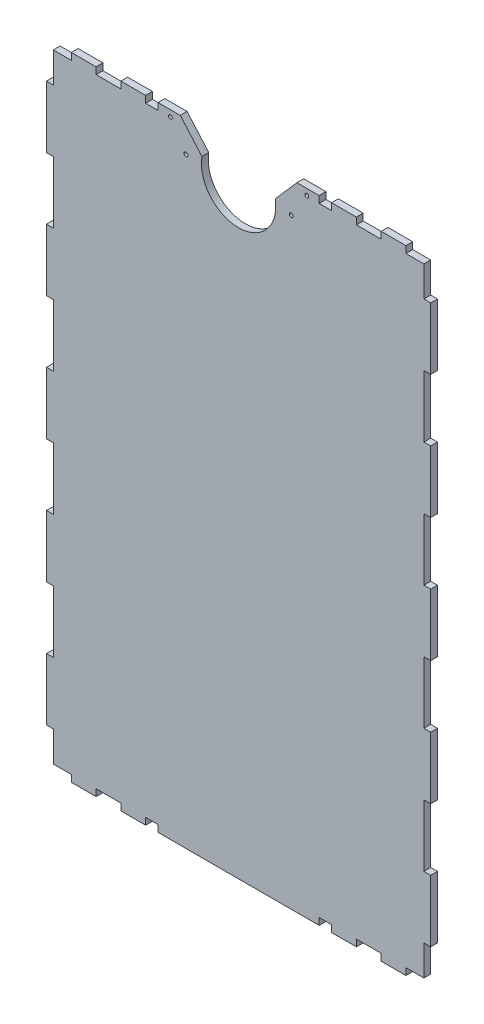
SolidWorks part; units mm, degrees
material "ﾁｰｸ材"
ref_plane "正面" through (0, 0, 0) normal (0, 0, 1) x (1, 0, 0)
ref_plane "平面" through (0, 0, 0) normal (0, 1, 0) x (1, 0, 0)
ref_plane "右側面" through (0, 0, 0) normal (1, 0, 0) x (0, 0, -1)
sketch "ｽｹｯﾁ1" plane through (0, 0, 0) normal (0, 0, 1) x (1, 0, 0)
  line L1 (155, 255) -> (-155, 255)
  line L2 (155, 255) -> (155, -255)
  line L3 (155, -255) -> (-155, -255)
  line L4 (-155, 255) -> (-155, -255)
  line L5 (155, 255) -> (-155, -255) construction
  line L6 (155, -255) -> (-155, 255) construction
  point P0 (0, 0)
  dimension "D1" = 310
  dimension "D2" = 510
extrude "ﾎﾞｽ - 押し出し1" add sketch "ｽｹｯﾁ1" along normal blind 5.5
sketch "ｽｹｯﾁ2" plane through (0, 0, 5.5) normal (0, 0, 1) x (1, 0, 0)
  line L0 (155, -255) -> (155, 255) construction
  line L1 (155, 25) -> (149.5, 25)
  line L2 (155, 25) -> (155, 75)
  line L3 (155, 75) -> (149.5, 75)
  line L4 (149.5, 25) -> (149.5, 75)
  line L9 (155, -75) -> (149.5, -75)
  line L10 (155, -75) -> (155, -25)
  line L11 (155, -25) -> (149.5, -25)
  line L12 (149.5, -75) -> (149.5, -25)
  line L13 (155, 125) -> (149.5, 125)
  line L14 (155, 125) -> (155, 175)
  line L15 (155, 175) -> (149.5, 175)
  line L16 (149.5, 125) -> (149.5, 175)
  line L17 (155, -175) -> (149.5, -175)
  line L18 (155, -175) -> (155, -125)
  line L19 (155, -125) -> (149.5, -125)
  line L20 (149.5, -175) -> (149.5, -125)
  line L21 (155, 225) -> (149.5, 225)
  line L22 (155, 225) -> (155, 275)
  line L23 (155, 275) -> (149.5, 275)
  line L24 (149.5, 225) -> (149.5, 275)
  line L25 (155, -275) -> (149.5, -275)
  line L26 (155, -275) -> (155, -225)
  line L27 (155, -225) -> (149.5, -225)
  line L28 (149.5, -275) -> (149.5, -225)
  line L29 (-149.5, 25) -> (-155, 25)
  line L30 (-149.5, 25) -> (-149.5, 75)
  line L31 (-149.5, 75) -> (-155, 75)
  line L32 (-155, 25) -> (-155, 75)
  line L33 (-149.5, -75) -> (-155, -75)
  line L34 (-149.5, -75) -> (-149.5, -25)
  line L35 (-149.5, -25) -> (-155, -25)
  line L36 (-155, -75) -> (-155, -25)
  line L37 (-149.5, 125) -> (-155, 125)
  line L38 (-149.5, 125) -> (-149.5, 175)
  line L39 (-149.5, 175) -> (-155, 175)
  line L40 (-155, 125) -> (-155, 175)
  line L41 (-149.5, -175) -> (-155, -175)
  line L42 (-149.5, -175) -> (-149.5, -125)
  line L43 (-149.5, -125) -> (-155, -125)
  line L44 (-155, -175) -> (-155, -125)
  line L45 (-149.5, 225) -> (-155, 225)
  line L46 (-149.5, 225) -> (-149.5, 275)
  line L47 (-149.5, 275) -> (-155, 275)
  line L48 (-155, 225) -> (-155, 275)
  line L49 (-149.5, -275) -> (-155, -275)
  line L50 (-149.5, -275) -> (-149.5, -225)
  line L51 (-149.5, -225) -> (-155, -225)
  line L52 (-155, -275) -> (-155, -225)
  line L53 (-155, 255) -> (-155, -255) construction
  point P53 (-152.25, 25)
  dimension "D1" = 5.5
  dimension "D2" = 50
  dimension "D3" = 25
  dimension "D4" = 50
  dimension "D5" = 50
  dimension "D6" = 50
  dimension "D7" = 50
  dimension "D8" = 50
  dimension "D9" = 5.5
  dimension "D10" = 50
  dimension "D11" = 50
  dimension "D12" = 50
  dimension "D13" = 50
  dimension "D14" = 50
  dimension "D15" = 50
  dimension "D16" = 25
extrude "ｶｯﾄ - 押し出し1" cut sketch "ｽｹｯﾁ2" against normal through all
sketch "ｽｹｯﾁ3" plane through (0, 0, 5.5) normal (0, 0, 1) x (1, 0, 0)
  line L0 (47.0333, 255) -> (29.5804, 235)
  line L2 (149.5, 255) -> (-149.5, 255) construction
  line L3 (47.0333, 255) -> (-47.0333, 255)
  line L4 (-47.0333, 255) -> (-29.5804, 235)
  arc A1 (29.5804, 235) -> (-29.5804, 235) centre (0, 230) cw
  dimension "D1" = 30
  dimension "D2" = 25
  dimension "D3" = 19
  dimension "D4" = 19
  dimension "D5" = 5
  dimension "D6" = 5
extrude "ｶｯﾄ - 押し出し2" cut sketch "ｽｹｯﾁ3" against normal through all
sketch "ｽｹｯﾁ5" plane through (0, 0, 5.5) normal (0, 0, 1) x (1, 0, 0)
  circle A0 centre (-42.5, 230) radius 1.6
  circle A1 centre (42.5, 230) radius 1.6
  point P4 (0, 230)
  dimension "D1" = 3.2
  dimension "D2" = 42.5
  dimension "D3" = 42.5
extrude "ｶｯﾄ - 押し出し3" cut sketch "ｽｹｯﾁ5" against normal through all
sketch "ｽｹｯﾁ6" plane through (0, 0, 5.5) normal (0, 0, 1) x (1, 0, 0)
  line L0 (149.5, 255) -> (47.0333, 255) construction
  circle A0 centre (55, 250) radius 1.55
  circle A1 centre (-55, 250) radius 1.55
  dimension "D1" = 3.1
  dimension "D3" = 5
  dimension "D2" = 55
  dimension "D4" = 55
extrude "ｶｯﾄ - 押し出し4" cut sketch "ｽｹｯﾁ6" against normal through all
sketch "ｽｹｯﾁ7" plane through (0, 0, 5.5) normal (0, 0, 1) x (1, 0, 0)
  line L0 (149.5, 255) -> (47.0333, 255) construction
  line L1 (135, 255) -> (155, 255)
  line L2 (135, 255) -> (135, 249.5)
  line L3 (135, 249.5) -> (155, 249.5)
  line L4 (155, 255) -> (155, 249.5)
  line L5 (155, 175) -> (155, 225) construction
  line L6 (95, 255) -> (95, 249.5)
  line L7 (95, 255) -> (115, 255)
  line L8 (115, 255) -> (115, 249.5)
  line L9 (95, 249.5) -> (115, 249.5)
  line L10 (0, 0) -> (0, 80.2112) construction
  line L11 (75, 255) -> (65, 255)
  line L12 (75, 255) -> (75, 249.5)
  line L13 (75, 249.5) -> (65, 249.5)
  line L14 (65, 255) -> (65, 249.5)
  line L15 (0, 0) -> (-49.6238, 0) construction
  line L16 (-75, 249.5) -> (-65, 249.5)
  line L17 (-65, 255) -> (-65, 249.5)
  line L18 (-75, 255) -> (-65, 255)
  line L19 (-75, 255) -> (-75, 249.5)
  line L20 (-95, 255) -> (-115, 255)
  line L21 (-115, 255) -> (-115, 249.5)
  line L22 (-95, 249.5) -> (-115, 249.5)
  line L23 (-95, 255) -> (-95, 249.5)
  line L24 (-135, 249.5) -> (-155, 249.5)
  line L25 (-155, 255) -> (-155, 249.5)
  line L26 (-135, 255) -> (-155, 255)
  line L27 (-135, 255) -> (-135, 249.5)
  line L28 (-135, -255) -> (-135, -249.5)
  line L29 (-135, -255) -> (-155, -255)
  line L30 (-155, -255) -> (-155, -249.5)
  line L31 (-135, -249.5) -> (-155, -249.5)
  line L32 (-95, -255) -> (-95, -249.5)
  line L33 (-95, -249.5) -> (-115, -249.5)
  line L34 (-115, -255) -> (-115, -249.5)
  line L35 (-95, -255) -> (-115, -255)
  line L36 (-75, -255) -> (-75, -249.5)
  line L37 (-75, -255) -> (-65, -255)
  line L38 (-65, -255) -> (-65, -249.5)
  line L39 (-75, -249.5) -> (-65, -249.5)
  line L40 (75, -249.5) -> (65, -249.5)
  line L41 (65, -255) -> (65, -249.5)
  line L42 (75, -255) -> (65, -255)
  line L43 (75, -255) -> (75, -249.5)
  line L44 (95, -255) -> (115, -255)
  line L45 (115, -255) -> (115, -249.5)
  line L46 (95, -249.5) -> (115, -249.5)
  line L47 (95, -255) -> (95, -249.5)
  line L48 (135, -249.5) -> (155, -249.5)
  line L49 (155, -255) -> (155, -249.5)
  line L50 (135, -255) -> (155, -255)
  line L51 (135, -255) -> (135, -249.5)
  point P16 (75, 252.25)
  point P17 (115, 252.25)
  dimension "D1" = 5.5
  dimension "D2" = 20
  dimension "D4" = 10
  dimension "D5" = 20
  dimension "D6" = 20
  dimension "D3" = 2
extrude "ｶｯﾄ - 押し出し5" cut sketch "ｽｹｯﾁ7" against normal through all
